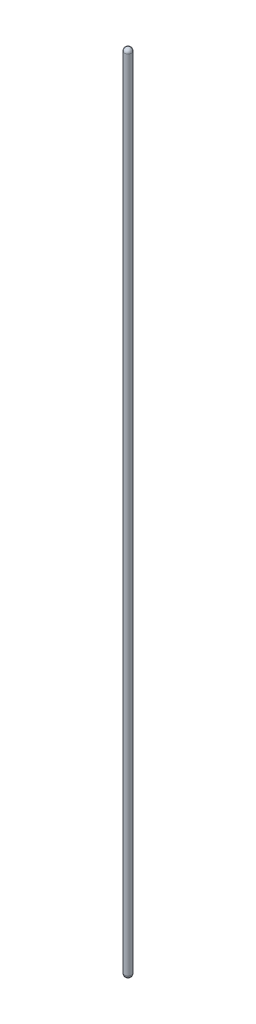
SolidWorks part; units mm, degrees
ref_plane "前视基准面" through (0, 0, 0) normal (0, 0, 1) x (1, 0, 0)
ref_plane "上视基准面" through (0, 0, 0) normal (0, 1, 0) x (1, 0, 0)
ref_plane "右视基准面" through (0, 0, 0) normal (1, 0, 0) x (0, 0, -1)
other "Configuration Table"
sketch "Sketch3" plane through (0, 0, 0) normal (0, 0, 1) x (1, 0, 0)
  line L2 (-9, 1000) -> (-9, -1000)
  line L3 (0, 3.9354) -> (0, -4.8367) construction
  line L4 (0, 1009) -> (0, -1009)
  arc A2 (-9, -1000) -> (0, -1009) centre (0, -1000) ccw
  arc A3 (-9, 1000) -> (0, 1009) centre (0, 1000) cw
  point P6 (-9, 0)
  dimension "D1" = 9
  dimension "D2" = 9
  dimension "D3" = 2000
revolve "Revolve4" add sketch "Sketch3" angle 360 about L3
